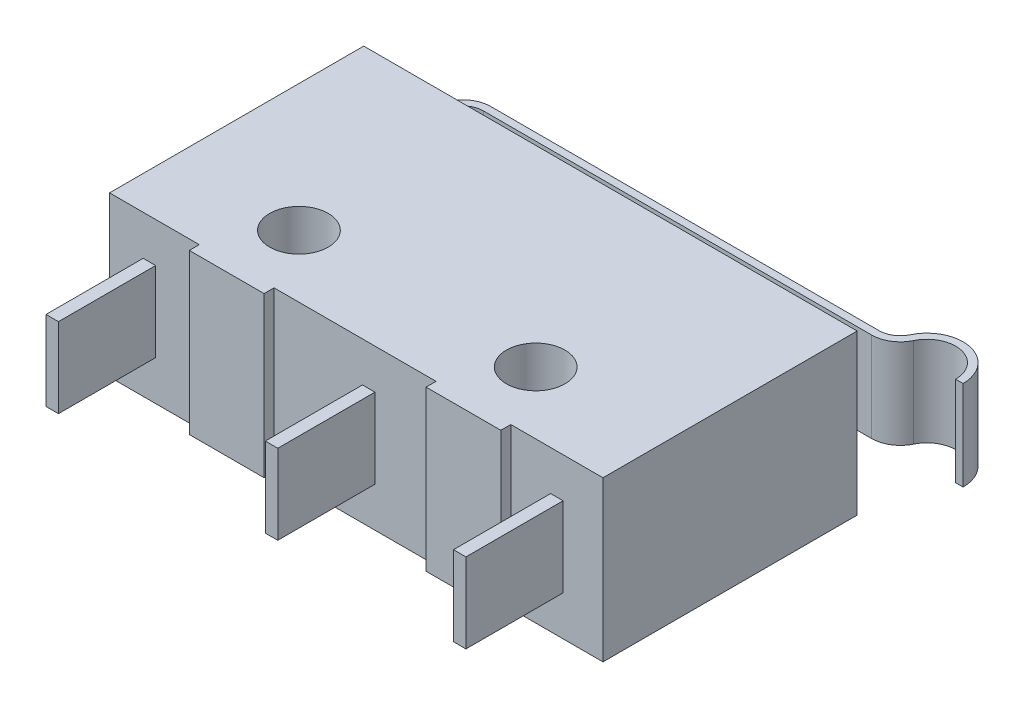
SolidWorks part; units mm, degrees
ref_plane "前视基准面" through (0, 0, 0) normal (0, 0, 1) x (1, 0, 0)
ref_plane "上视基准面" through (0, 0, 0) normal (0, 1, 0) x (1, 0, 0)
ref_plane "右视基准面" through (0, 0, 0) normal (1, 0, 0) x (0, 0, -1)
other "Configuration Table"
sketch "草图1" plane through (0, 0, 0) normal (0, 1, 0) x (1, 0, 0)
  line L1 (0, 0) -> (19.8, 0)
  line L2 (0, 0) -> (0, 10.2)
  line L3 (0, 10.2) -> (19.8, 10.2)
  line L4 (19.8, 0) -> (19.8, 10.2)
  line L5 (0, 0) -> (19.8, 10.2) construction
  line L6 (0, 10.2) -> (19.8, 0) construction
  point P4 (9.9, 5.1)
  dimension "D1" = 19.8
  dimension "D2" = 10.2
extrude "凸台-拉伸1" add sketch "草图1" along normal blind 6.4
sketch "草图2" plane through (0, 6.4, 0) normal (0, 1, 0) x (1, 0, 0)
  line L0 (5.1, 2.5) -> (14.6, 2.5) construction
  line L1 (0, 10.2) -> (0, 0) construction
  line L2 (0, 0) -> (19.8, 0) construction
  circle A0 centre (5.1, 2.5) radius 1.175
  circle A1 centre (14.6, 2.5) radius 1.175
  dimension "D1" = 5.1
  dimension "D4" = 2.35
  dimension "D2" = 9.5
  dimension "D3" = 2.5
extrude "切除-拉伸1" cut sketch "草图2" against normal up to next
ref_plane "基准面1" through (0, 3.2, 0) normal (0, 1, 0) x (1, 0, 0)
sketch "草图3" plane through (0, 3.2, 0) normal (0, 1, 0) x (1, 0, 0)
  line L0 (2.2538, 10.2) -> (2.2538, 10.9)
  line L1 (19.8, 10.2) -> (0, 10.2) construction
  line L2 (3.2538, 11.9) -> (18.8288, 11.9)
  line L3 (20.9, 13.2) -> (17.0781, 13.2) construction
  line L4 (0, 10.2) -> (0, 0) construction
  arc A0 (19.7293, 12.4652) -> (22.2, 11.9) centre (20.9, 11.9) cw
  circle A2 centre (14.6, 2.5) radius 1.175 construction
  circle A3 centre (5.1, 2.5) radius 1.175 construction
  arc A4 (2.2538, 10.9) -> (3.2538, 11.9) centre (3.2538, 10.9) cw
  arc A5 (18.8288, 11.9) -> (19.7293, 12.4652) centre (18.8288, 12.9) ccw
  point P11 (19.0257, 11.3868)
  point P12 (0, 0)
  point P15 (22.2, 11.9)
  point P16 (0, 0)
  dimension "D1" = 10.7
  dimension "D2" = 15.8
  dimension "D3" = 1.3
  dimension "D5" = 1
  dimension "D6" = 1
  dimension "D4" = 2.2538
extrude "拉伸-薄壁1" add sketch "草图3" along normal blind 1.8 and the other way blind 1.8 thin thin type mid plane wall 0.3
sketch "草图4" plane through (0, 3.2, 0) normal (0, 1, 0) x (1, 0, 0)
  line L0 (1.6, 0) -> (1.6, -3.9)
  line L1 (0, 0) -> (19.8, 0) construction
  line L2 (10.4, 0) -> (10.4, -3.9)
  line L3 (17.95, 0) -> (17.95, -3.9)
  line L4 (1.6, -3.9) -> (17.95, -3.9) construction
  line L5 (0, 10.2) -> (0, 0) construction
  circle A0 centre (5.1, 2.5) radius 1.175 construction
  point P10 (8.3072, -3.9)
  dimension "D1" = 6.4
  dimension "D2" = 1.6
  dimension "D3" = 8.8
  dimension "D4" = 7.55
extrude "拉伸-薄壁2" add sketch "草图4" along normal blind 1.6 and the other way blind 1.6 thin thin type mid plane wall 0.5
sketch "草图5" plane through (0, 6.4, 0) normal (0, 1, 0) x (1, 0, 0)
  line L0 (0, 0) -> (19.8, 0) construction
  line L1 (3.6, 0) -> (6.6, 0)
  line L2 (3.6, 0) -> (3.6, -0.4)
  line L3 (3.6, -0.4) -> (6.6, -0.4)
  line L4 (6.6, 0) -> (6.6, -0.4)
  line L5 (3.6, 0) -> (6.6, -0.4) construction
  line L6 (3.6, -0.4) -> (6.6, 0) construction
  line L7 (5.1, 2.5) -> (5.1, -0.2) construction
  line L8 (13.1, 0) -> (16.1, 0)
  line L9 (13.1, 0) -> (13.1, -0.4)
  line L10 (13.1, -0.4) -> (16.1, -0.4)
  line L11 (16.1, 0) -> (16.1, -0.4)
  line L12 (13.1, 0) -> (16.1, -0.4) construction
  line L13 (13.1, -0.4) -> (16.1, 0) construction
  line L14 (14.6, 2.5) -> (14.6, -0.2) construction
  point P4 (5.1, -0.2)
  point P11 (14.6, -0.2)
  dimension "D1" = 0.4
  dimension "D2" = 3
extrude "凸台-拉伸2" add sketch "草图5" against normal up to surface (6.4 mm away) up to face at (5.1, 0, -3.675)
